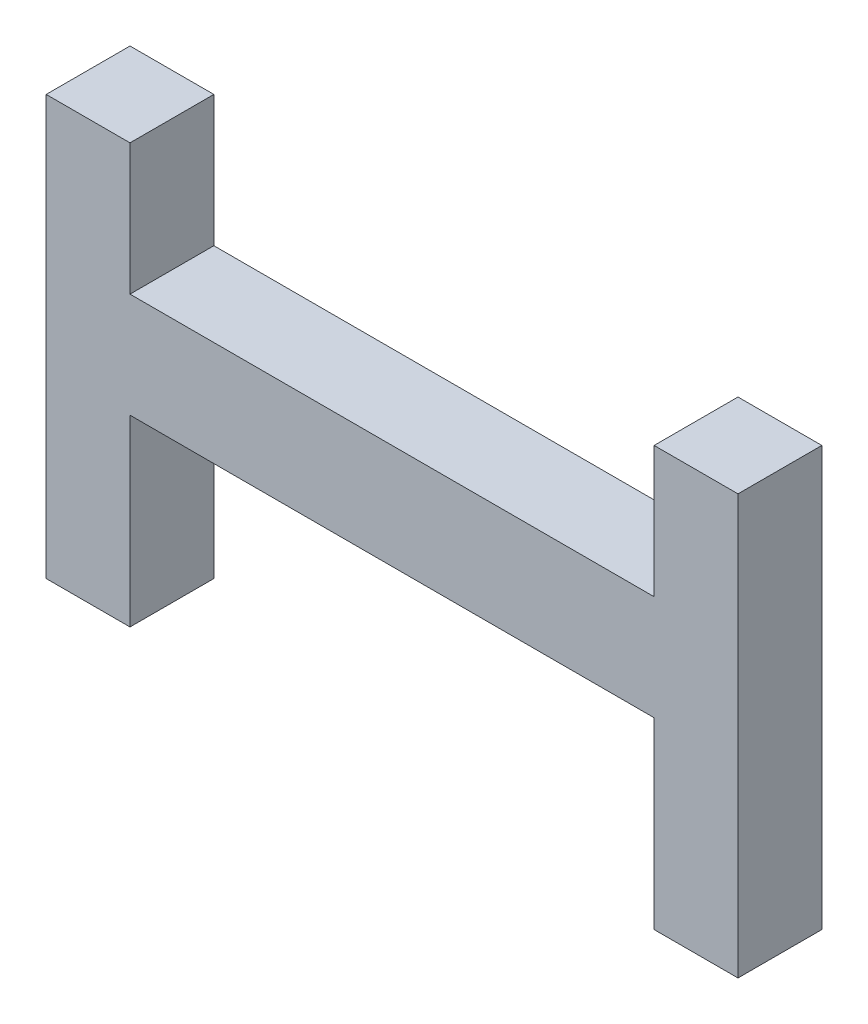
SolidWorks part; units mm, degrees
ref_plane "Front Plane" through (0, 0, 0) normal (0, 0, 1) x (1, 0, 0)
ref_plane "Top Plane" through (0, 0, 0) normal (0, 1, 0) x (1, 0, 0)
ref_plane "Right Plane" through (0, 0, 0) normal (1, 0, 0) x (0, 0, -1)
sketch "Sketch1" plane through (0, 0, 0) normal (0, 0, 1) x (1, 0, 0)
  line L0 (8.8251, 4) -> (8.8251, -4)
  line L1 (8.8251, -4) -> (7.225, -4)
  line L2 (7.225, -4) -> (7.225, -0.5)
  line L3 (7.225, -0.5) -> (-2.775, -0.5)
  line L4 (-2.775, -0.5) -> (-2.775, -4)
  line L5 (-2.775, -4) -> (-4.375, -4)
  line L6 (-4.375, -4) -> (-4.375, 4)
  line L7 (-4.375, 4) -> (-2.775, 4)
  line L8 (-2.775, 4) -> (-2.775, 1.5)
  line L9 (-2.775, 1.5) -> (7.225, 1.5)
  line L10 (7.225, 1.5) -> (7.225, 4)
  line L11 (7.225, 4) -> (8.8251, 4)
extrude "Boss-Extrude1" add sketch "Sketch1" along normal blind 1.6
